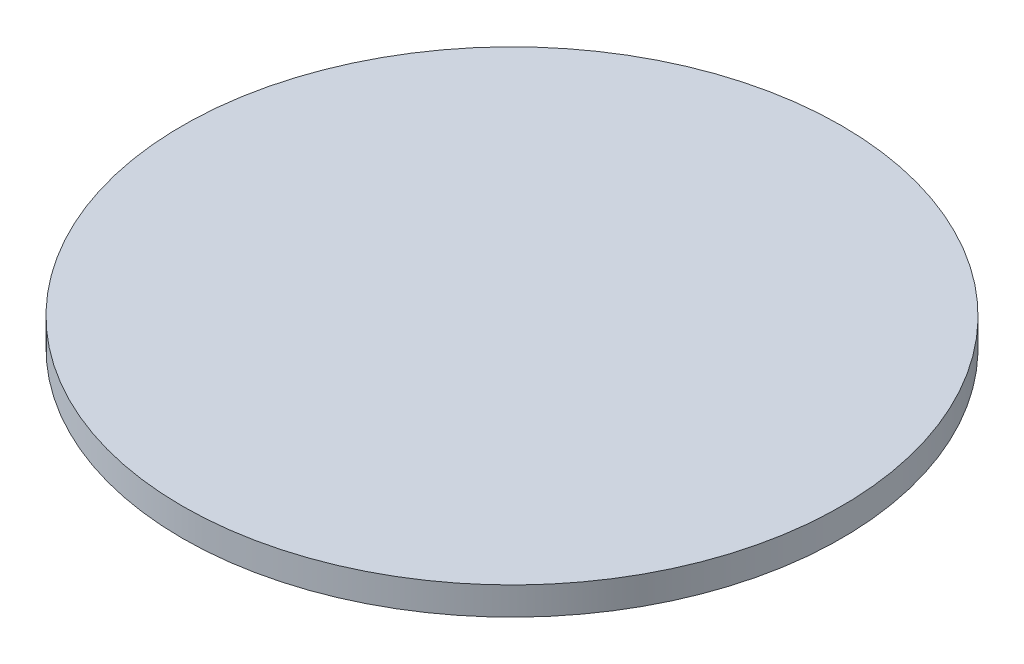
SolidWorks part; units mm, degrees
ref_plane "Front Plane" through (0, 0, 0) normal (0, 0, 1) x (1, 0, 0)
ref_plane "Top Plane" through (0, 0, 0) normal (0, 1, 0) x (1, 0, 0)
ref_plane "Right Plane" through (0, 0, 0) normal (1, 0, 0) x (0, 0, -1)
sketch "Sketch1" plane through (0, 0, 0) normal (0, 1, 0) x (1, 0, 0)
  circle A0 centre (0, 0) radius 6
  dimension "D1" = 12
extrude "Boss-Extrude1" add sketch "Sketch1" along normal mid plane 0.508
